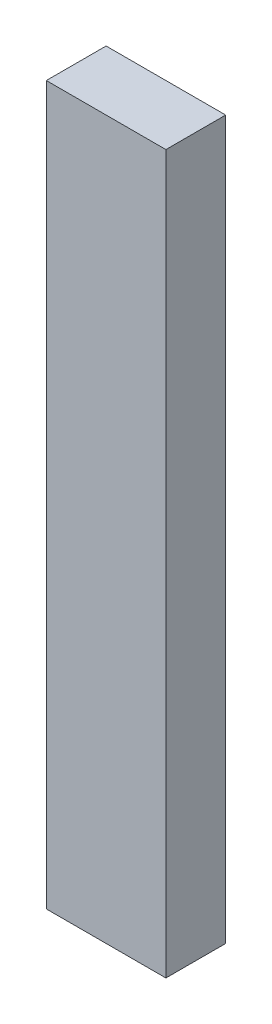
SolidWorks part; units mm, degrees
ref_plane "Front Plane" through (0, 0, 0) normal (0, 0, 1) x (1, 0, 0)
ref_plane "Top Plane" through (0, 0, 0) normal (0, 1, 0) x (1, 0, 0)
ref_plane "Right Plane" through (0, 0, 0) normal (1, 0, 0) x (0, 0, -1)
sketch "Sketch1" plane through (0, 0, 0) normal (0, 1, 0) x (1, 0, 0)
  line L1 (0, 0) -> (101.6, 0)
  line L2 (0, 0) -> (0, -50.8)
  line L3 (0, -50.8) -> (101.6, -50.8)
  line L4 (101.6, 0) -> (101.6, -50.8)
  dimension "D1" = 50.8
  dimension "D2" = 101.6
extrude "Boss-Extrude1" add sketch "Sketch1" along normal blind 609.6
